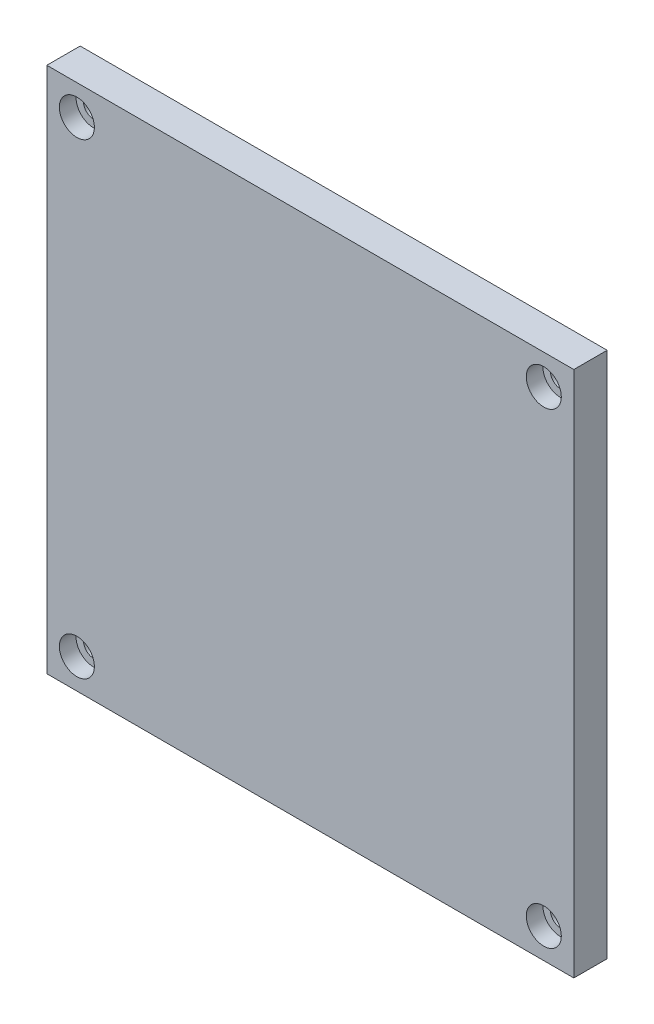
SolidWorks part; units mm, degrees
ref_plane "Front Plane" through (0, 0, 0) normal (0, 0, 1) x (1, 0, 0)
ref_plane "Top Plane" through (0, 0, 0) normal (0, 1, 0) x (1, 0, 0)
ref_plane "Right Plane" through (0, 0, 0) normal (1, 0, 0) x (0, 0, -1)
sketch "Sketch1" plane through (0, 0, 0) normal (0, 0, 1) x (1, 0, 0)
  line L1 (-52.07, -29.21) -> (29.21, -29.21)
  line L2 (-52.07, -29.21) -> (-52.07, 52.07)
  line L3 (-52.07, 52.07) -> (29.21, 52.07)
  line L4 (29.21, -29.21) -> (29.21, 52.07)
  line L8 (-46.99, 46.99) -> (24.13, 46.99) construction
  line L9 (24.13, 46.99) -> (24.13, -24.13) construction
  line L10 (24.13, -24.13) -> (-46.99, -24.13) construction
  line L11 (-46.99, -24.13) -> (-46.99, 46.99) construction
  circle A0 centre (-46.99, 46.99) radius 1.524
  circle A1 centre (-46.99, -24.13) radius 1.524
  circle A2 centre (24.13, -24.13) radius 1.524
  circle A3 centre (24.13, 46.99) radius 1.524
  point P4 (0, 0)
  point P5 (-24.13, 24.13)
  point P6 (0, 0)
  point P7 (0, 0)
  point P8 (-35.9027, 65.6352)
  point P9 (24.13, 11.43)
  point P10 (29.21, 11.43)
  point P11 (-11.43, -24.13)
  point P24 (-11.43, -29.21)
  dimension "D5" = 3.048
  dimension "D1" = 81.28
  dimension "D2" = 81.28
  dimension "D3" = 5.08
  dimension "D4" = 5.08
extrude "Boss-Extrude1" add sketch "Sketch1" along normal up to surface (5.08 mm away)
sketch "Sketch2" plane through (0, 0, 5.08) normal (0, 0, 1) x (1, 0, 0)
  circle A0 centre (-46.99, -24.13) radius 2.667
  circle A1 centre (-46.99, 46.99) radius 2.667
  circle A2 centre (24.13, 46.99) radius 2.667
  circle A3 centre (24.13, -24.13) radius 2.667
  circle A4 centre (-46.99, 46.99) radius 1.524 construction
  circle A5 centre (24.13, 46.99) radius 1.524 construction
  circle A6 centre (-46.99, -24.13) radius 1.524 construction
  point P12 (0, 0)
  point P13 (0, 0)
  point P16 (0, 0)
  point P19 (0, 0)
  dimension "D1" = 5.334
extrude "Cut-Extrude1" cut sketch "Sketch2" against normal blind 2.54
sketch "Sketch3" plane through (0, 0, 5.08) normal (0, 0, 1) x (1, 0, 0)
  line L0 (29.21, 52.07) -> (-52.07, 52.07) construction
  line L1 (-51.562, 51.562) -> (28.702, 51.562)
  line L2 (-51.562, 51.562) -> (-51.562, -28.702)
  line L3 (-51.562, -28.702) -> (28.702, -28.702)
  line L4 (28.702, 51.562) -> (28.702, -28.702)
  line L5 (-52.07, -29.21) -> (-52.07, 52.07) construction
  line L6 (-52.07, 52.07) -> (29.21, 52.07) construction
  line L8 (-52.07, 52.07) -> (29.21, 52.07)
  line L9 (-52.07, 52.07) -> (-52.07, -29.21)
  line L10 (-52.07, -29.21) -> (29.21, -29.21)
  line L11 (29.21, 52.07) -> (29.21, -29.21)
  point P8 (-11.43, 52.07)
  point P11 (-11.43, 51.562)
  point P12 (-51.562, 11.43)
  point P13 (-52.07, 11.43)
  dimension "D1" = 0.508
  dimension "D2" = 0.508
extrude "Cut-Extrude2" cut sketch "Sketch3" against normal through all
